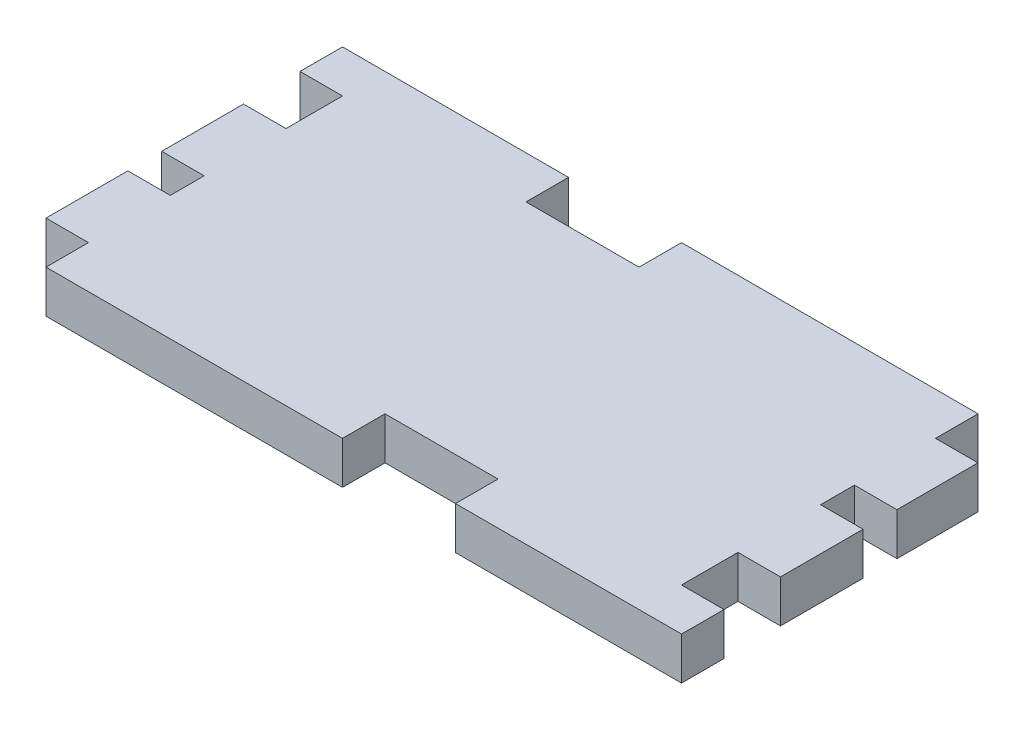
SolidWorks part; units mm, degrees
ref_plane "Front Plane" through (0, 0, 0) normal (0, 0, 1) x (1, 0, 0)
ref_plane "Top Plane" through (0, 0, 0) normal (0, 1, 0) x (1, 0, 0)
ref_plane "Right Plane" through (0, 0, 0) normal (1, 0, 0) x (0, 0, -1)
sketch "Sketch2" plane through (0, 0, 0) normal (0, 1, 0) x (1, 0, 0)
  line L1 (-38.1, -19.05) -> (38.1, -19.05)
  line L2 (-38.1, -19.05) -> (-38.1, 19.05)
  line L3 (-38.1, 19.05) -> (38.1, 19.05)
  line L4 (38.1, -19.05) -> (38.1, 19.05)
  line L5 (-38.1, -19.05) -> (38.1, 19.05) construction
  line L6 (-38.1, 19.05) -> (38.1, -19.05) construction
  point P0 (0, 0)
  dimension "D1" = 76.2
  dimension "D2" = 38.1
extrude "Boss-Extrude1" add sketch "Sketch2" along normal blind 4.7752
sketch "Sketch3" plane through (0, 4.7752, 0) normal (0, 1, 0) x (1, 0, 0)
  line L0 (-38.1, 19.05) -> (-33.3248, 19.05) construction
  line L1 (38.1, 19.05) -> (-38.1, 19.05) construction
  line L2 (-33.3248, 19.05) -> (-33.3248, -19.05) construction
  line L3 (-38.1, -19.05) -> (38.1, -19.05) construction
  line L4 (38.1, 19.05) -> (33.3248, 19.05) construction
  line L5 (33.3248, 19.05) -> (33.3248, -19.05) construction
  line L6 (38.1, -19.05) -> (38.1, -14.2748) construction
  line L7 (38.1, -19.05) -> (38.1, 19.05) construction
  line L8 (38.1, -14.2748) -> (-38.1, -14.2748) construction
  line L9 (-38.1, 19.05) -> (-38.1, -19.05) construction
  line L10 (-38.1, -14.2748) -> (-38.1, 19.05) construction
  line L11 (-38.1, 19.05) -> (-38.1, 14.2748) construction
  line L12 (-38.1, 14.2748) -> (38.1, 14.2748) construction
  line L13 (-33.3248, -14.2748) -> (-33.3248, 7.9248) construction
  line L14 (-38.1, 14.2748) -> (-33.3248, 14.2748)
  line L15 (-38.1, 14.2748) -> (-38.1, 7.9248)
  line L16 (-38.1, 7.9248) -> (-33.3248, 7.9248)
  line L17 (-33.3248, 14.2748) -> (-33.3248, 7.9248)
  line L18 (-38.1, -14.2748) -> (-33.3248, -14.2748)
  line L19 (-38.1, -14.2748) -> (-38.1, -19.05)
  line L20 (-38.1, -19.05) -> (-33.3248, -19.05)
  line L21 (-33.3248, -14.2748) -> (-33.3248, -19.05)
  line L22 (-33.3248, -3.175) -> (-38.1, -3.175) construction
  line L23 (33.3248, 19.05) -> (38.1, 19.05)
  line L24 (-38.1, -5.08) -> (-33.3248, -5.08)
  line L25 (-38.1, -5.08) -> (-38.1, -1.27)
  line L26 (-38.1, -1.27) -> (-33.3248, -1.27)
  line L27 (-33.3248, -5.08) -> (-33.3248, -1.27)
  line L28 (-38.1, -5.08) -> (-33.3248, -1.27) construction
  line L29 (-38.1, -1.27) -> (-33.3248, -5.08) construction
  line L30 (33.3248, 19.05) -> (33.3248, 14.2748)
  line L31 (33.3248, 14.2748) -> (38.1, 14.2748)
  line L32 (38.1, 19.05) -> (38.1, 14.2748)
  line L33 (33.3248, -7.9248) -> (38.1, -7.9248)
  line L34 (33.3248, -7.9248) -> (33.3248, -14.2748)
  line L35 (33.3248, -14.2748) -> (38.1, -14.2748)
  line L36 (38.1, -7.9248) -> (38.1, -14.2748)
  line L41 (38.1, -7.9248) -> (38.1, 1.3542) construction
  line L43 (38.1, 1.3542) -> (33.3248, 1.3542)
  line L44 (38.1, 1.3542) -> (38.1, 5.1642)
  line L45 (38.1, 5.1642) -> (33.3248, 5.1642)
  line L46 (33.3248, 1.3542) -> (33.3248, 5.1642)
  line L47 (0, 14.2748) -> (-12.7, 14.2748)
  line L48 (0, 14.2748) -> (0, 19.05)
  line L49 (0, 19.05) -> (-12.7, 19.05)
  line L50 (-12.7, 14.2748) -> (-12.7, 19.05)
  line L51 (0, -14.2748) -> (12.7, -14.2748)
  line L52 (0, -14.2748) -> (0, -19.05)
  line L53 (0, -19.05) -> (12.7, -19.05)
  line L54 (12.7, -14.2748) -> (12.7, -19.05)
  point P31 (-35.7124, -3.175)
  dimension "D1" = 4.7752
  dimension "D2" = 4.7752
  dimension "D3" = 4.7752
  dimension "D4" = 4.7752
  dimension "D5" = 6.35
  dimension "D6" = 3.81
  dimension "D7" = 3.81
  dimension "D8" = 6.35
  dimension "D9" = 12.7
  dimension "D10" = 12.7
  dimension "D11" = 4.7752
extrude "Cut-Extrude1" cut sketch "Sketch3" against normal blind 6.35
